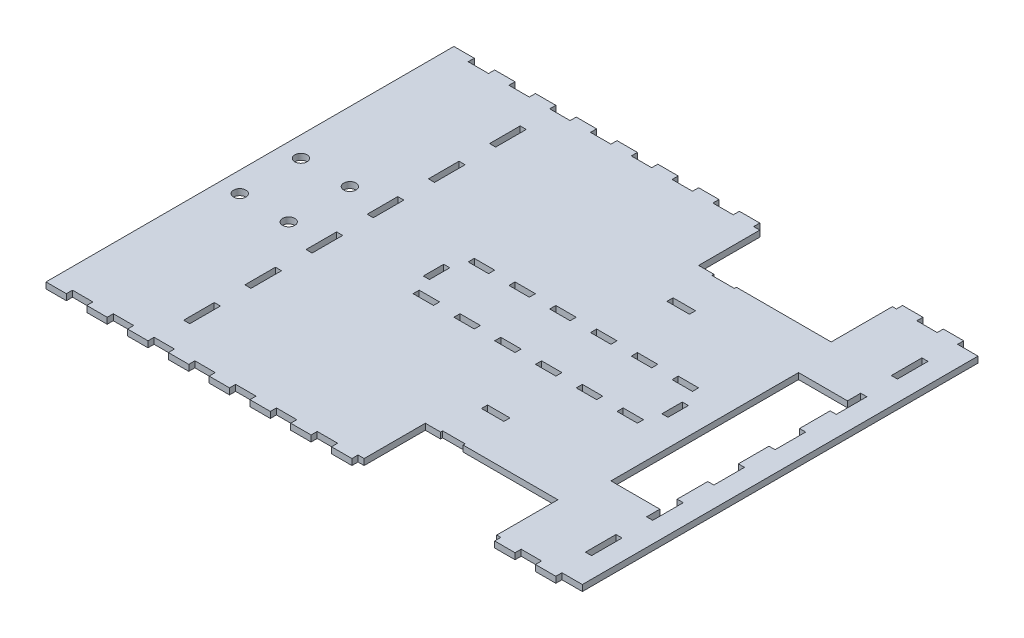
SolidWorks part; units mm, degrees
ref_plane "Front Plane" through (0, 0, 0) normal (0, 0, 1) x (1, 0, 0)
ref_plane "Top Plane" through (0, 0, 0) normal (0, 1, 0) x (1, 0, 0)
ref_plane "Right Plane" through (0, 0, 0) normal (1, 0, 0) x (0, 0, -1)
sketch "Sketch3" plane through (0, 0, 0) normal (0, 1, 0) x (1, 0, 0)
  line L0 (0, 0) -> (-300, 0) construction
  line L1 (-300, -97) -> (-300, 97)
  line L2 (-290, 100) -> (-300, 100)
  line L3 (-290, 97) -> (-290, 100)
  line L4 (-280, 97) -> (-290, 97)
  line L5 (-300, 100) -> (-300, 97)
  line L6 (-270, 100) -> (-280, 100)
  line L7 (-270, 97) -> (-270, 100)
  line L8 (-260, 97) -> (-270, 97)
  line L9 (-280, 100) -> (-280, 97)
  line L10 (-250, 100) -> (-260, 100)
  line L11 (-250, 97) -> (-250, 100)
  line L12 (-240, 97) -> (-250, 97)
  line L13 (-260, 100) -> (-260, 97)
  line L14 (-150, -100) -> (-150, 100) construction
  line L15 (-230, 100) -> (-240, 100)
  line L16 (-230, 97) -> (-230, 100)
  line L17 (-220, 97) -> (-230, 97)
  line L18 (-240, 100) -> (-240, 97)
  line L19 (-210, 100) -> (-220, 100)
  line L20 (-210, 97) -> (-210, 100)
  line L21 (-200, 97) -> (-210, 97)
  line L22 (-40, 97) -> (-40, -97)
  line L23 (-50, 37.5) -> (-53, 37.5)
  line L24 (-50, 7.5) -> (-53, 7.5)
  line L25 (-50, -45.947) -> (-50, 45.947) construction
  line L26 (-247, 37.5) -> (-250, 37.5)
  line L27 (-247, 7.5) -> (-250, 7.5)
  line L28 (-247, 48.5) -> (-247, -48.5) construction
  line L29 (-247, 48.5) -> (-223, 48.5) construction
  line L30 (-223, 48.5) -> (-223, -48.5) construction
  line L31 (-210, 15) -> (-90, 15) construction
  line L32 (-90, 15) -> (-90, 5) construction
  line L33 (-50, 7.5) -> (-50, 22.5)
  line L34 (-220, 100) -> (-220, 97)
  line L35 (-190, 100) -> (-200, 100)
  line L36 (-190, 97) -> (-190, 100)
  line L37 (-180, 97) -> (-190, 97)
  line L38 (-200, 100) -> (-200, 97)
  line L39 (-170, 100) -> (-180, 100)
  line L40 (-170, 97) -> (-170, 100)
  line L41 (-160, 97) -> (-170, 97)
  line L42 (-180, 100) -> (-180, 97)
  line L43 (-150, 100) -> (-160, 100)
  line L44 (-150, 97) -> (-150, 100)
  line L45 (-140, 97) -> (-150, 97)
  line L46 (-160, 100) -> (-160, 97)
  line L47 (-130, 100) -> (-140, 100)
  line L48 (-130, 97) -> (-130, 100)
  line L49 (-120, 97) -> (-130, 97)
  line L50 (-140, 100) -> (-140, 97)
  line L51 (-110, 100) -> (-120, 100)
  line L52 (-110, 97) -> (-110, 100)
  line L53 (-100, 97) -> (-110, 97)
  line L54 (-120, 100) -> (-120, 97)
  line L55 (-90, 100) -> (-100, 100)
  line L56 (-90, 97) -> (-90, 100)
  line L57 (-80, 97) -> (-90, 97)
  line L58 (-100, 100) -> (-100, 97)
  line L59 (-70, 100) -> (-80, 100)
  line L60 (-70, 97) -> (-70, 100)
  line L61 (-60, 97) -> (-70, 97)
  line L62 (-80, 100) -> (-80, 97)
  line L63 (-50, 100) -> (-60, 100)
  line L64 (-50, 97) -> (-50, 100)
  line L65 (-40, 97) -> (-50, 97)
  line L66 (-60, 100) -> (-60, 97)
  line L67 (-50, 22.5) -> (-53, 22.5)
  line L68 (-210, -15) -> (-90, -15) construction
  line L69 (-53, 7.5) -> (-53, 22.5)
  line L70 (-50, 37.5) -> (-50, 52.5)
  line L71 (-50, 52.5) -> (-53, 52.5)
  line L72 (-53, 37.5) -> (-53, 52.5)
  line L73 (-50, 67.5) -> (-53, 67.5)
  line L74 (-50, 67.5) -> (-50, 82.5)
  line L75 (-50, 82.5) -> (-53, 82.5)
  line L76 (-60, -100) -> (-60, -97)
  line L77 (-40, -97) -> (-50, -97)
  line L78 (-50, -97) -> (-50, -100)
  line L79 (-50, -100) -> (-60, -100)
  line L80 (-80, -100) -> (-80, -97)
  line L81 (-60, -97) -> (-70, -97)
  line L82 (-70, -97) -> (-70, -100)
  line L83 (-70, -100) -> (-80, -100)
  line L84 (-100, -100) -> (-100, -97)
  line L85 (-80, -97) -> (-90, -97)
  line L86 (-90, -97) -> (-90, -100)
  line L87 (-90, -100) -> (-100, -100)
  line L88 (-120, -100) -> (-120, -97)
  line L89 (-100, -97) -> (-110, -97)
  line L90 (-110, -97) -> (-110, -100)
  line L91 (-110, -100) -> (-120, -100)
  line L92 (-140, -100) -> (-140, -97)
  line L93 (-120, -97) -> (-130, -97)
  line L94 (-130, -97) -> (-130, -100)
  line L95 (-130, -100) -> (-140, -100)
  line L96 (-160, -100) -> (-160, -97)
  line L97 (-140, -97) -> (-150, -97)
  line L98 (-150, -97) -> (-150, -100)
  line L99 (-150, -100) -> (-160, -100)
  line L100 (-180, -100) -> (-180, -97)
  line L101 (-160, -97) -> (-170, -97)
  line L102 (-170, -97) -> (-170, -100)
  line L103 (-170, -100) -> (-180, -100)
  line L104 (-200, -100) -> (-200, -97)
  line L105 (-180, -97) -> (-190, -97)
  line L106 (-190, -97) -> (-190, -100)
  line L107 (-190, -100) -> (-200, -100)
  line L108 (-247, -48.5) -> (-223, -48.5) construction
  line L109 (-247, 7.5) -> (-247, 22.5)
  line L110 (-220, -100) -> (-220, -97)
  line L111 (-53, 67.5) -> (-53, 82.5)
  line L112 (-53, -67.5) -> (-53, -82.5)
  line L113 (-50, -82.5) -> (-53, -82.5)
  line L114 (-200, -97) -> (-210, -97)
  line L115 (-210, -97) -> (-210, -100)
  line L116 (-210, -100) -> (-220, -100)
  line L117 (-240, -100) -> (-240, -97)
  line L118 (-220, -97) -> (-230, -97)
  line L119 (-230, -97) -> (-230, -100)
  line L120 (-230, -100) -> (-240, -100)
  line L121 (-50, -67.5) -> (-50, -82.5)
  line L122 (-260, -100) -> (-260, -97)
  line L123 (-240, -97) -> (-250, -97)
  line L124 (-250, -97) -> (-250, -100)
  line L125 (-250, -100) -> (-260, -100)
  line L126 (-280, -100) -> (-280, -97)
  line L127 (-260, -97) -> (-270, -97)
  line L128 (-270, -97) -> (-270, -100)
  line L129 (-270, -100) -> (-280, -100)
  line L130 (-300, -100) -> (-300, -97)
  line L131 (-210, 15) -> (-210, -15) construction
  line L132 (-115, 15) -> (-125, 15)
  line L133 (-90, 5) -> (-93, 5)
  line L134 (-90, 5) -> (-90, -5)
  line L135 (-90, -5) -> (-93, -5)
  line L136 (-93, 5) -> (-93, -5)
  line L137 (-95, 15) -> (-105, 15)
  line L138 (-95, 15) -> (-95, 12)
  line L139 (-95, 12) -> (-105, 12)
  line L140 (-105, 15) -> (-105, 12)
  line L141 (-115, 12) -> (-125, 12)
  line L142 (-125, 15) -> (-125, 12)
  line L143 (-135, 15) -> (-145, 15)
  line L144 (-135, 12) -> (-145, 12)
  line L145 (-145, 15) -> (-145, 12)
  line L146 (-155, 15) -> (-165, 15)
  line L147 (-155, 12) -> (-165, 12)
  line L148 (-165, 15) -> (-165, 12)
  line L149 (-175, 15) -> (-185, 15)
  line L150 (-175, 12) -> (-185, 12)
  line L151 (-185, 15) -> (-185, 12)
  line L152 (-195, 15) -> (-205, 15)
  line L153 (-195, 12) -> (-205, 12)
  line L154 (-205, 15) -> (-205, 12)
  line L155 (-195, 12) -> (-195, 15)
  line L156 (-175, 12) -> (-175, 15)
  line L157 (-155, 12) -> (-155, 15)
  line L158 (-135, 12) -> (-135, 15)
  line L159 (-115, 12) -> (-115, 15)
  line L160 (-207, 5) -> (-207, -5)
  line L161 (-210, -5) -> (-207, -5)
  line L162 (-210, 5) -> (-210, -5)
  line L163 (-210, 5) -> (-207, 5)
  line L164 (-115, -12) -> (-115, -15)
  line L165 (-135, -12) -> (-135, -15)
  line L166 (-155, -12) -> (-155, -15)
  line L167 (-175, -12) -> (-175, -15)
  line L168 (-195, -12) -> (-195, -15)
  line L169 (-205, -15) -> (-205, -12)
  line L170 (-195, -12) -> (-205, -12)
  line L171 (-195, -15) -> (-205, -15)
  line L172 (-185, -15) -> (-185, -12)
  line L173 (-175, -12) -> (-185, -12)
  line L174 (-175, -15) -> (-185, -15)
  line L175 (-165, -15) -> (-165, -12)
  line L176 (-155, -12) -> (-165, -12)
  line L177 (-155, -15) -> (-165, -15)
  line L178 (-145, -15) -> (-145, -12)
  line L179 (-135, -12) -> (-145, -12)
  line L180 (-135, -15) -> (-145, -15)
  line L181 (-125, -15) -> (-125, -12)
  line L182 (-115, -12) -> (-125, -12)
  line L183 (-105, -15) -> (-105, -12)
  line L184 (-95, -12) -> (-105, -12)
  line L185 (-95, -15) -> (-95, -12)
  line L186 (-95, -15) -> (-105, -15)
  line L187 (-115, -15) -> (-125, -15)
  line L188 (-247, 22.5) -> (-250, 22.5)
  line L189 (-250, 7.5) -> (-250, 22.5)
  line L190 (-247, 37.5) -> (-247, 52.5)
  line L191 (-247, 52.5) -> (-250, 52.5)
  line L192 (-250, 37.5) -> (-250, 52.5)
  line L193 (-247, 67.5) -> (-250, 67.5)
  line L194 (-247, 67.5) -> (-247, 82.5)
  line L195 (-247, 82.5) -> (-250, 82.5)
  line L196 (-250, 67.5) -> (-250, 82.5)
  line L197 (-250, -67.5) -> (-250, -82.5)
  line L198 (-247, -82.5) -> (-250, -82.5)
  line L199 (-247, -67.5) -> (-247, -82.5)
  line L200 (-247, -67.5) -> (-250, -67.5)
  line L201 (-250, -37.5) -> (-250, -52.5)
  line L202 (-247, -52.5) -> (-250, -52.5)
  line L203 (-247, -37.5) -> (-247, -52.5)
  line L204 (-250, -7.5) -> (-250, -22.5)
  line L205 (-247, -22.5) -> (-250, -22.5)
  line L206 (-247, -7.5) -> (-247, -22.5)
  line L207 (-247, -7.5) -> (-250, -7.5)
  line L208 (-247, -37.5) -> (-250, -37.5)
  line L209 (-50, -67.5) -> (-53, -67.5)
  line L210 (-53, -37.5) -> (-53, -52.5)
  line L211 (-50, -52.5) -> (-53, -52.5)
  line L212 (-50, -37.5) -> (-50, -52.5)
  line L213 (-53, -7.5) -> (-53, -22.5)
  line L214 (-50, -22.5) -> (-53, -22.5)
  line L215 (-50, -7.5) -> (-50, -22.5)
  line L216 (-50, -7.5) -> (-53, -7.5)
  line L217 (-50, -37.5) -> (-53, -37.5)
  line L231 (-280, -97) -> (-290, -97)
  line L232 (-290, -97) -> (-290, -100)
  line L233 (-290, -100) -> (-300, -100)
  circle A0 centre (-290, 15) radius 3
  circle A1 centre (-266, 15) radius 3
  circle A2 centre (-266, -15) radius 3
  circle A3 centre (-290, -15) radius 3
  point P31 (-250, 36)
  point P80 (-91.5, 0)
  point P82 (-150, 0)
  point P126 (-223, 0)
  point P128 (-250, 18)
  point P129 (-50, 0)
  point P150 (-150, -15)
  point P151 (-150, 15)
  point P183 (-208.5, 0)
  point P212 (-223, 18)
  point P218 (-223, 36)
  dimension "D17" = 6
  dimension "D18" = 6
  dimension "D1" = 300
  dimension "D4" = 7.5
  dimension "D5" = 100
  dimension "D6" = 97
  dimension "D7" = 15
  dimension "D8" = 97
  dimension "D9" = 3
  dimension "D10" = 3
  dimension "D11" = 48.5
  dimension "D12" = 24
  dimension "D13" = 60
  dimension "D14" = 15
  dimension "D15" = 24
  dimension "D16" = 15
  dimension "D19" = 194
  dimension "D20" = 10
  dimension "D21" = 3
  dimension "D22" = 7.5
  dimension "D23" = 15
  dimension "D24" = 3
  dimension "D25" = 3
  dimension "D29" = 10
  dimension "D30" = 3
  dimension "D31" = 10
  dimension "D32" = 3
  dimension "D33" = 10
  dimension "D34" = 5
  dimension "D35" = 6
  dimension "D36" = 3
extrude "Boss-Extrude1" add sketch "Sketch3" along normal blind 3
sketch "Sketch4" plane through (0, 3, 0) normal (0, 1, 0) x (1, 0, 0)
  line L0 (-53, 5) -> (-53, 15) construction
  line L1 (-53, 46) -> (-77, 46)
  line L2 (-53, 46) -> (-53, -46)
  line L3 (-53, -46) -> (-77, -46)
  line L4 (-77, 46) -> (-77, -46)
  line L5 (-90, 0) -> (0, 0) construction
  line L6 (-90, 5) -> (-90, -5) construction
  dimension "D1" = 92
  dimension "D2" = 24
  dimension "D3" = 46
extrude "Cut-Extrude1" cut sketch "Sketch4" against normal blind 10
sketch "Sketch5" plane through (0, 3, 0) normal (0, 1, 0) x (1, 0, 0)
  line L0 (-82, 0) -> (-82, 67) construction
  line L1 (-77, 46) -> (-77, -46) construction
  line L2 (-82, 67) -> (-128.5, 67)
  line L3 (-82, 67) -> (-82, 97)
  line L4 (-82, 97) -> (-147, 97)
  line L5 (-147, 67) -> (-147, 97)
  line L6 (-82, 97) -> (-82, 117.024)
  line L7 (-110, 100) -> (-120, 100) construction
  line L8 (-82, 0) -> (-300, 0) construction
  line L9 (-300, 100) -> (-300, -100) construction
  line L10 (-147, -67) -> (-147, -97)
  line L11 (-82, -97) -> (-147, -97)
  line L12 (-82, -67) -> (-82, -97)
  line L13 (-82, -67) -> (-128.5, -67)
  line L14 (-114.5, -67) -> (-114.5, -47) construction
  line L15 (-114.5, -47) -> (-128.5, -47) construction
  line L16 (-128.5, -47) -> (-128.5, -44)
  line L17 (-128.5, -44) -> (-139.5, -44)
  line L18 (-139.5, -44) -> (-139.5, -47)
  line L19 (-139.5, -47) -> (-128.5, -47)
  line L20 (-128.5, -67) -> (-128.5, -66)
  line L21 (-128.5, -66) -> (-139.5, -66)
  line L22 (-139.5, -66) -> (-139.5, -67)
  line L23 (-139.5, -67) -> (-147, -67)
  line L24 (-114.5, 47) -> (-128.5, 47) construction
  line L25 (-114.5, 67) -> (-114.5, 47) construction
  line L26 (-139.5, 66) -> (-139.5, 67)
  line L27 (-128.5, 66) -> (-139.5, 66)
  line L28 (-128.5, 67) -> (-128.5, 66)
  line L29 (-139.5, 47) -> (-128.5, 47)
  line L30 (-139.5, 44) -> (-139.5, 47)
  line L31 (-128.5, 44) -> (-139.5, 44)
  line L32 (-128.5, 47) -> (-128.5, 44)
  line L33 (-139.5, 67) -> (-147, 67)
  dimension "D1" = 5
  dimension "D2" = 30
  dimension "D3" = 3
  dimension "D4" = 65
  dimension "D5" = 14
  dimension "D6" = 3
  dimension "D7" = 11
  dimension "D8" = 20
  dimension "D9" = 1
extrude "Cut-Extrude2" cut sketch "Sketch5" against normal blind 10 contours L5 L2 L3 L4 | L12 L13 L10 L11 | L31 L30 L29 L32 | L17 L18 L19 L16
